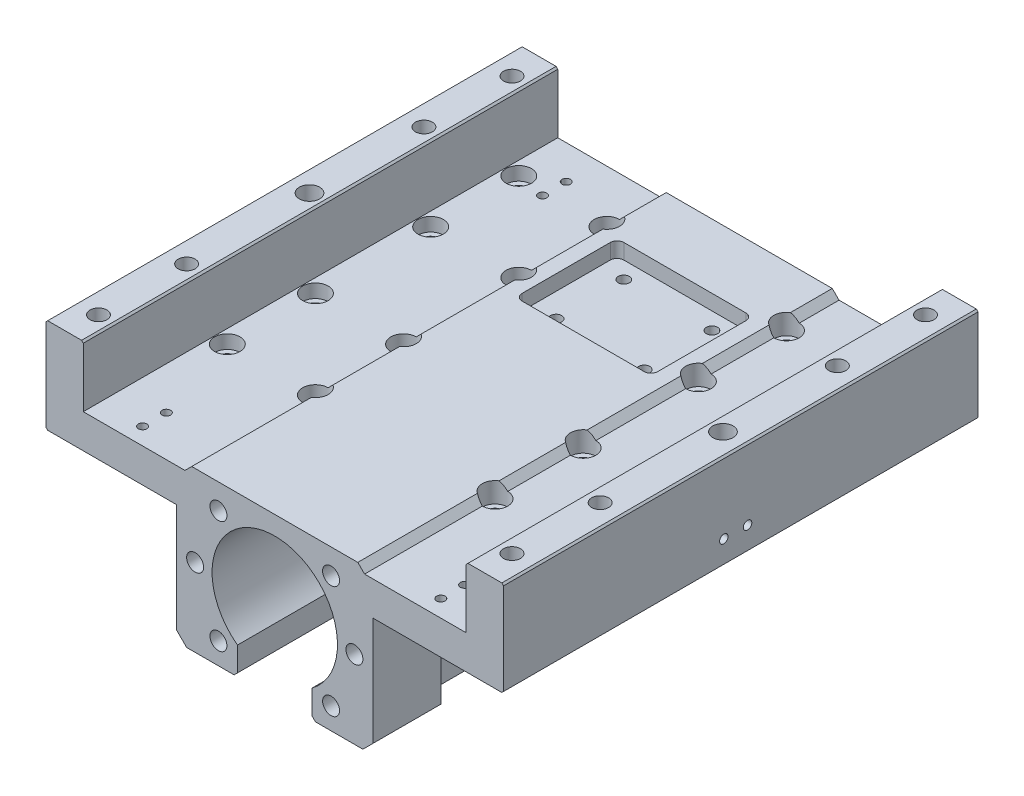
SolidWorks part; units mm, degrees
ref_plane "前视" through (0, 0, 0) normal (0, 0, 1) x (1, 0, 0)
ref_plane "上视" through (0, 0, 0) normal (0, 1, 0) x (1, 0, 0)
ref_plane "右视" through (0, 0, 0) normal (1, 0, 0) x (0, 0, -1)
sketch "草图1" plane through (0, 0, 0) normal (0, 0, 1) x (1, 0, 0)
  line L1 (-67.5, 40) -> (67.5, 40)
  line L2 (-67.5, 40) -> (-67.5, -23)
  line L3 (-67.5, -23) -> (67.5, -23)
  line L4 (67.5, 40) -> (67.5, -23)
  dimension "D1" = 135
  dimension "D2" = 63
  dimension "D3" = 67.5
  dimension "D4" = 23
extrude "凸台-拉伸1" add sketch "草图1" along normal blind 140
sketch "草图2" plane through (0, 0, 140) normal (0, 0, 1) x (1, 0, 0)
  line L0 (-67.5, 40) -> (-67.5, -23) construction
  line L1 (29, 12) -> (67.5, 12)
  line L2 (29, 12) -> (29, -23)
  line L3 (29, -23) -> (67.5, -23)
  line L4 (67.5, 12) -> (67.5, -23)
  line L5 (-67.5, 12) -> (-29, 12)
  line L6 (-67.5, 12) -> (-67.5, -23)
  line L7 (-67.5, -23) -> (-29, -23)
  line L8 (-29, 12) -> (-29, -23)
  line L9 (-67.5, -23) -> (67.5, -23) construction
  dimension "D1" = 35
  dimension "D2" = 38.5
  dimension "D3" = 38.5
extrude "切除-拉伸1" cut sketch "草图2" against normal up to next
sketch "草图3" plane through (0, 0, 140) normal (0, 0, 1) x (1, 0, 0)
  line L0 (-56.5, 40) -> (-56.5, 22)
  line L1 (67.5, 40) -> (-67.5, 40) construction
  line L2 (-56.5, 22) -> (-26.5, 22)
  line L3 (-26.5, 22) -> (-24.5, 24)
  line L4 (-24.5, 24) -> (24.5, 24)
  line L5 (26.5, 22) -> (24.5, 24)
  line L6 (26.5, 22) -> (56.5, 22)
  line L7 (56.5, 22) -> (56.5, 40)
  line L8 (56.5, 40) -> (-56.5, 40)
  line L9 (-67.5, 40) -> (-67.5, 12) construction
  line L10 (67.5, 12) -> (67.5, 40) construction
  line L11 (0, 0) -> (0, 58.7585) construction
  point P18 (0, 24)
  dimension "D1" = 11
  dimension "D2" = 11
  dimension "D3" = 18
  dimension "D4" = 53
  dimension "D7" = 2
  dimension "D8" = 24.5
extrude "切除-拉伸2" cut sketch "草图3" against normal up to next
sketch "草图4" plane through (0, 0, 140) normal (0, 0, 1) x (1, 0, 0)
  line L0 (-11, -23) -> (-11, -14.8745)
  line L1 (-29, -23) -> (29, -23) construction
  line L2 (0, 0) -> (0, -31.2762) construction
  line L3 (11, -23) -> (11, -14.8745)
  line L4 (-11, -23) -> (11, -23)
  arc A0 (11, -14.8745) -> (-11, -14.8745) centre (0, 0) ccw
  dimension "D1" = 37
  dimension "D2" = 11
extrude "切除-拉伸3" cut sketch "草图4" against normal blind 70
sketch "草图5" plane through (0, 0, 70) normal (0, 0, 1) x (1, 0, 0)
  line L0 (-11, -23) -> (-11, -9.4472)
  line L1 (11, -23) -> (11, -9.4472)
  line L2 (-11, -23) -> (11, -23)
  arc A0 (11, -9.4472) -> (-11, -9.4472) centre (0, 0) ccw
  dimension "D1" = 29
extrude "切除-拉伸4" cut sketch "草图5" against normal up to next
chamfer "倒角1" distance 3 angle 45 2 edges at (29, -23, 70) (-29, -23, 70)
chamfer "倒角2" distance 0.5 angle 45 6 edges at (67.5, 12, 70) (-67.5, 12, 70) (-67.5, 40, 70) (-56.5, 40, 70) (56.5, 40, 70) (67.5, 40, 70)
chamfer "倒角3" distance 1 angle 45 2 edges at (-11, -23, 70) (11, -23, 70)
sketch "草图7" plane through (0, 0, 0) normal (0, 0, -1) x (-1, 0, 0)
  line L0 (-12, -23) -> (-26, -23) construction
  line L1 (-29, 12) -> (-21, 12)
  line L2 (-29, 12) -> (-29, -23)
  line L3 (-29, -23) -> (-21, -23)
  line L4 (-21, 12) -> (-21, -23)
  line L5 (26, -23) -> (12, -23) construction
  line L6 (29, 12) -> (21, 12)
  line L7 (29, 12) -> (29, -23)
  line L8 (29, -23) -> (21, -23)
  line L9 (21, 12) -> (21, -23)
  dimension "D1" = 21
  dimension "D2" = 21
extrude "切除-拉伸5" cut sketch "草图7" against normal blind 120
sketch "草图8" plane through (0, 24, 0) normal (0, 1, 0) x (1, 0, 0)
  line L0 (24.5, 0) -> (-24.5, 0) construction
  line L1 (-18, -19) -> (18, -19)
  line L2 (-20, -21) -> (-20, -47)
  line L3 (-18, -49) -> (18, -49)
  line L4 (20, -21) -> (20, -47)
  arc A0 (-20, -47) -> (-18, -49) centre (-18, -47) ccw
  arc A1 (18, -49) -> (20, -47) centre (18, -47) ccw
  arc A2 (18, -19) -> (20, -21) centre (18, -21) cw
  arc A3 (-18, -19) -> (-20, -21) centre (-18, -21) ccw
  point P11 (20, -49)
  point P14 (20, -19)
  point P17 (-20, -19)
  dimension "D5" = 2
  dimension "D1" = 40
  dimension "D2" = 30
  dimension "D3" = 19
  dimension "D4" = 20
extrude "切除-拉伸6" cut sketch "草图8" against normal blind 4.5
sketch "草图9" plane through (0, 19.5, 0) normal (0, 1, 0) x (1, 0, 0)
  line L0 (-15.1329, -24) -> (15.1329, -24) construction
  line L1 (-13, -22.9543) -> (-13, -44.1609) construction
  line L2 (-15.1329, -44) -> (15.1329, -44) construction
  line L3 (13, -22.9543) -> (13, -44.1609) construction
  line L4 (18, -19) -> (-18, -19) construction
  dimension "D1" = 20
  dimension "D2" = 26
  dimension "D3" = 13
  dimension "D4" = 5
hole_wizard "M4 螺纹孔1" positions "3D草图1" profile "草图10" tap size "M4" standard "Gb"
sketch3d "3D草图1"
  line L0 (-15.1329, 19.5, 24) -> (15.1329, 19.5, 24) construction
  line L1 (13, 19.5, 22.9543) -> (13, 19.5, 44.1609) construction
  line L2 (-13, 19.5, 22.9543) -> (-13, 19.5, 44.1609) construction
  line L3 (-15.1329, 19.5, 44) -> (15.1329, 19.5, 44) construction
  point P0 (13, 19.5, 24)
  point P6 (-13.0066, 19.5, 24)
  point P8 (-13, 19.5, 44)
  point P14 (13, 19.5, 44)
sketch "草图10" plane through (13, 19.5, 24) normal (1, 0, 0) x (0, 0, 1)
  line L0 (0, 0) -> (0, 8.9914)
  line L1 (0, 8.9914) -> (1.65, 8)
  line L2 (1.65, 8) -> (1.65, 0)
  line L5 (1.65, 0) -> (0, 0)
  line L10 (0, 8.9914) -> (-1.65, 8) construction
  line L11 (0, -6.35) -> (0, 107.95) construction
  dimension "螺纹孔钻头直径" = 3.3
  dimension "螺纹孔钻头深度" = 8
  dimension "导头角度" = 118
cosmetic thread "孔螺蚊线1" parameters "D1"=8, "D2"=4
cosmetic thread "孔螺蚊线2" parameters "D1"=8, "D2"=4
cosmetic thread "孔螺蚊线3" parameters "D1"=8, "D2"=4
cosmetic thread "孔螺蚊线4" parameters "D1"=8, "D2"=4
sketch "草图11" plane through (0, 40, 0) normal (0, 1, 0) x (1, 0, 0)
  line L0 (-61, 9.1603) -> (-61, -146.6699) construction
  line L2 (-75.8507, -9) -> (-47.8223, -9) construction
  line L3 (-90.2026, -35) -> (-47.8223, -35) construction
  line L4 (-77.2032, -105) -> (-46.6667, -105) construction
  line L5 (-75.8507, -131) -> (-52.0845, -131) construction
  dimension "D1" = 61
  dimension "D2" = 9
  dimension "D3" = 26
  dimension "D4" = 70
  dimension "D5" = 26
hole_wizard "M6 螺纹孔1" positions "3D草图2" profile "草图12" tap size "M6" standard "Gb"
sketch3d "3D草图2"
  line L0 (-61, 40, -9.1603) -> (-61, 40, 146.6699) construction
  line L1 (-75.8507, 40, 9) -> (-47.8223, 40, 9) construction
  line L2 (-90.2026, 40, 35) -> (-47.8223, 40, 35) construction
  line L3 (-75.8507, 40, 131) -> (-52.0845, 40, 131) construction
  line L4 (-77.2032, 40, 105) -> (-46.6667, 40, 105) construction
  point P0 (-61, 40, 9)
  point P6 (-61, 40, 35)
  point P10 (-61, 40, 131)
  point P14 (-61, 40, 105)
sketch "草图12" plane through (-61, 40, 9) normal (1, 0, 0) x (0, 0, 1)
  line L0 (0, 0) -> (0, 16.5022)
  line L1 (0, 16.5022) -> (2.5, 15)
  line L2 (2.5, 15) -> (2.5, 0)
  line L5 (2.5, 0) -> (0, 0)
  line L10 (0, 16.5022) -> (-2.5, 15) construction
  line L11 (0, -6.35) -> (0, 107.95) construction
  dimension "螺纹孔钻头直径" = 5
  dimension "螺纹孔钻头深度" = 15
  dimension "导头角度" = 118
cosmetic thread "孔螺蚊线5" parameters "D1"=15, "D2"=6
cosmetic thread "孔螺蚊线6" parameters "D1"=15, "D2"=6
cosmetic thread "孔螺蚊线7" parameters "D1"=15, "D2"=6
cosmetic thread "孔螺蚊线8" parameters "D1"=15, "D2"=6
sketch "草图13" plane through (0, 40, 0) normal (0, 1, 0) x (1, 0, 0)
  line L0 (-61, 9.1603) -> (-61, -146.6699) construction
  circle A0 centre (-61, -68.7548) radius 3
  dimension "D1" = 6
extrude "切除-拉伸7" cut sketch "草图13" against normal blind 8
mirror "镜向1" about plane through (0, 0, 0) normal (1, 0, 0) of "切除-拉伸7", "M6 螺纹孔1"
sketch "草图14" plane through (0, 24, 0) normal (0, 1, 0) x (1, 0, 0)
  line L1 (-26.5, 0) -> (-56.5, 0) construction
  line L2 (-26.5, 0) -> (-26.5, -140) construction
  circle A0 centre (-52.5, -15.5) radius 3.75
  circle A1 centre (-26.5, -15.5) radius 3.75
  circle A2 centre (-52.5, -41.5) radius 3.75
  circle A3 centre (-26.5, -41.5) radius 3.75
  dimension "D1" = 7.5
  dimension "D3" = 7.5
  dimension "D5" = 7.5
  dimension "D6" = 7.5
  dimension "D2" = 15.5
  dimension "D4" = 26
  dimension "D7" = 26
  dimension "D8" = 26
extrude "切除-拉伸8" cut sketch "草图14" against normal blind 6
sketch "草图15" plane through (0, 18, 0) normal (0, 1, 0) x (1, 0, 0)
  circle A0 centre (-26.5, -15.5) radius 2.25
  circle A1 centre (-26.5, -41.5) radius 2.25
  circle A2 centre (-52.5, -41.5) radius 2.25
  circle A3 centre (-52.5, -15.5) radius 2.25
  dimension "D1" = 4.5
  dimension "D2" = 4.5
  dimension "D3" = 4.5
  dimension "D4" = 4.5
extrude "切除-拉伸9" cut sketch "草图15" against normal up to next
pattern_linear "阵列(线性)1" count 2 spacing 60 along (0, 0, 1) of "切除-拉伸8", "切除-拉伸9"
mirror "镜向2" about plane through (0, 0, 0) normal (1, 0, 0) of "阵列(线性)1", "切除-拉伸9", "切除-拉伸8"
sketch "草图16" plane through (0, 22, 0) normal (0, 1, 0) x (1, 0, 0)
  line L0 (-26.5, 0) -> (-56.5, 0) construction
  line L1 (0, 0) -> (0, -14.6155) construction
  line L2 (24.5, 0) -> (-24.5, 0) construction
  circle A0 centre (-44, -10) radius 1.25
  circle A1 centre (-44, -17) radius 1.25
  circle A2 centre (44, -17) radius 1.25
  circle A3 centre (44, -10) radius 1.25
  dimension "D4" = 2.5
  dimension "D5" = 2.5
  dimension "D1" = 44
  dimension "D2" = 7
  dimension "D3" = 10
extrude "切除-拉伸10" cut sketch "草图16" against normal up to next
cosmetic thread "装饰螺纹线1" parameters "D1"=5, "D2"=3
cosmetic thread "装饰螺纹线2" parameters "D1"=5, "D2"=3
cosmetic thread "装饰螺纹线3" parameters "D1"=5, "D2"=3
cosmetic thread "装饰螺纹线4" parameters "D1"=5, "D2"=3
pattern_linear "阵列(线性)2" count 2 spacing 118 along (0, 0, 1) of "切除-拉伸10"
sketch "草图17" plane through (0, 0, 140) normal (0, 0, 1) x (1, 0, 0)
  line L0 (0, 0) -> (32.1403, 0) construction
  line L1 (0, 0) -> (0, 30.3615) construction
  line L2 (0, 0) -> (28.5509, 28.5509) construction
  line L3 (0, 0) -> (-28.5509, 28.5509) construction
  line L4 (0, 0) -> (-28.5509, -28.5509) construction
  line L5 (0, 0) -> (28.5509, -28.5509) construction
  line L6 (0, 0) -> (-42.1122, 0) construction
  circle A0 centre (0, 0) radius 23.5 construction
  dimension "D2" = 47
  dimension "D1" = 45
hole_wizard "M6 螺纹孔2" positions "3D草图3" profile "草图18" tap size "M6" standard "Gb"
sketch3d "3D草图3"
  line L0 (0, 0, 140) -> (28.5509, 28.5509, 140) construction
  line L1 (0, 0, 140) -> (-28.5509, 28.5509, 140) construction
  line L2 (0, 0, 140) -> (-42.1122, 0, 140) construction
  line L3 (0, 0, 140) -> (-28.5509, -28.5509, 140) construction
  line L4 (0, 0, 140) -> (28.5509, -28.5509, 140) construction
  line L5 (0, 0, 140) -> (32.1403, 0, 140) construction
  circle A0 centre (0, 0, 140) radius 23.5 construction
  point P0 (16.617, 16.617, 140)
  point P6 (0, 0, 163.5)
  point P7 (-16.617, 16.617, 140)
  point P11 (-23.5, 0, 140)
  point P15 (-16.617, -16.617, 140)
  point P19 (16.617, -16.617, 140)
  point P23 (23.5, 0, 140)
sketch "草图18" plane through (16.617, 16.617, 140) normal (1, 0, 0) x (0, -1, 0)
  line L0 (0, 0) -> (0, 16.5022)
  line L1 (0, 16.5022) -> (2.5, 15)
  line L2 (2.5, 15) -> (2.5, 0)
  line L5 (2.5, 0) -> (0, 0)
  line L10 (0, 16.5022) -> (-2.5, 15) construction
  line L11 (0, -6.35) -> (0, 107.95) construction
  dimension "螺纹孔钻头直径" = 5
  dimension "螺纹孔钻头深度" = 15
  dimension "导头角度" = 118
cosmetic thread "孔螺蚊线9" parameters "D1"=15, "D2"=6
cosmetic thread "孔螺蚊线10" parameters "D1"=15, "D2"=6
cosmetic thread "孔螺蚊线11" parameters "D1"=15, "D2"=6
cosmetic thread "孔螺蚊线12" parameters "D1"=15, "D2"=6
cosmetic thread "孔螺蚊线13" parameters "D1"=15, "D2"=6
cosmetic thread "孔螺蚊线14" parameters "D1"=15, "D2"=6
sketch "草图19" plane through (-67.5, 0, 0) normal (-1, 0, 0) x (0, 0, 1)
  line L0 (-4.3775, 19) -> (141.5138, 19) construction
  line L2 (0, 40) -> (140, 40) construction
  line L3 (68, 32.2749) -> (68, 15.5222) construction
  line L4 (75, 30.7403) -> (75, 15.5222) construction
  line L5 (0, 39.5) -> (0, 22) construction
  point P11 (0, 30.75)
  dimension "D1" = 21
  dimension "D2" = 68
  dimension "D3" = 7
hole_wizard "M3 螺纹孔1" positions "3D草图4" profile "草图20" tap size "M3" standard "Gb"
sketch3d "3D草图4"
  line L0 (-67.5, 19, -4.3775) -> (-67.5, 19, 141.5138) construction
  line L1 (-67.5, 32.2749, 68) -> (-67.5, 15.5222, 68) construction
  line L2 (-67.5, 30.7403, 75) -> (-67.5, 15.5222, 75) construction
  point P0 (-67.5, 19, 68)
  point P6 (-67.5, 19, 75)
sketch "草图20" plane through (-67.5, 19, 68) normal (0, 1, 0) x (0, 0, 1)
  line L0 (0, 0) -> (0, 8.7511)
  line L1 (0, 8.7511) -> (1.25, 8)
  line L2 (1.25, 8) -> (1.25, 0)
  line L5 (1.25, 0) -> (0, 0)
  line L10 (0, 8.7511) -> (-1.25, 8) construction
  line L11 (0, -6.35) -> (0, 107.95) construction
  dimension "螺纹孔钻头直径" = 2.5
  dimension "螺纹孔钻头深度" = 8
  dimension "导头角度" = 118
cosmetic thread "孔螺蚊线15" parameters "D1"=8, "D2"=3
cosmetic thread "孔螺蚊线16" parameters "D1"=8, "D2"=3
mirror "镜向3" about plane through (0, 0, 0) normal (1, 0, 0) of "M3 螺纹孔1"
